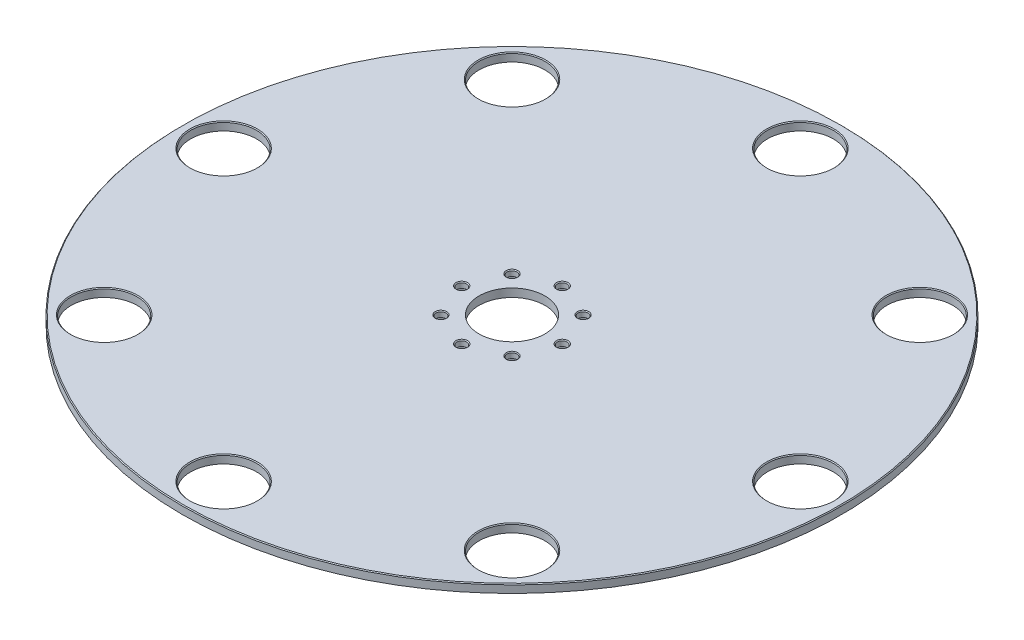
SolidWorks part; units mm, degrees
ref_plane "Front Plane" through (0, 0, 0) normal (0, 0, 1) x (1, 0, 0)
ref_plane "Top Plane" through (0, 0, 0) normal (0, 1, 0) x (1, 0, 0)
ref_plane "Right Plane" through (0, 0, 0) normal (1, 0, 0) x (0, 0, -1)
sketch "Sketch2" plane through (0, 0, 0) normal (0, 1, 0) x (1, 0, 0)
  line L0 (0, 409.7546) -> (0, -366.7272) construction
  line L1 (-380.7051, 0) -> (447.7899, 0) construction
  circle A0 centre (0, 0) radius 400
  circle A1 centre (0, 0) radius 40
  circle A2 centre (0, 350) radius 40
  circle A3 centre (247.4874, 247.4874) radius 40
  circle A4 centre (350, 0) radius 40
  circle A5 centre (247.4874, -247.4874) radius 40
  circle A6 centre (0, -350) radius 40
  circle A7 centre (-247.4874, -247.4874) radius 40
  circle A8 centre (-350, 0) radius 40
  circle A9 centre (-247.4874, 247.4874) radius 40
  point P26 (0, 0)
  point P52 (0, 0)
  dimension "D1" = 350
  dimension "D2" = 80
  dimension "D3" = 80
  dimension "D5" = 800
  dimension "D4" = 8
extrude "Boss-Extrude10" add sketch "Sketch2" along normal blind 10
chamfer "Chamfer1" distance 1 angle 45 9 edges at (-247.4874, 10, 287.4874) (0, 10, 390) (247.4874, 10, 287.4874) (350, 10, 40) (247.4874, 10, -207.4874) (0, 10, -310) (-247.4874, 10, -207.4874) (-350, 10, 40) (0, 10, 400)
sketch "Sketch13" plane through (0, 10, 0) normal (0, 1, 0) x (1, 0, 0)
  line L0 (0, 0) -> (-373.6419, 0) construction
  circle A0 centre (-61, 0) radius 6
  circle A1 centre (-43.1335, 43.1335) radius 6
  circle A2 centre (0, 61) radius 6
  circle A3 centre (43.1335, 43.1335) radius 6
  circle A4 centre (61, 0) radius 6
  circle A5 centre (43.1335, -43.1335) radius 6
  circle A6 centre (0, -61) radius 6
  circle A7 centre (-43.1335, -43.1335) radius 6
  point P21 (0, 0)
  dimension "D1" = 61
  dimension "D2" = 12
  dimension "D3" = 8
extrude "Cut-Extrude1" cut sketch "Sketch13" against normal blind 7
sketch "Sketch14" plane through (0, 0, 0) normal (0, -1, 0) x (1, 0, 0)
  line L0 (0, 0) -> (-132.8482, 0) construction
  circle A0 centre (-61, 0) radius 4
  circle A1 centre (-43.1335, 43.1335) radius 4
  circle A2 centre (0, 61) radius 4
  circle A3 centre (43.1335, 43.1335) radius 4
  circle A4 centre (61, 0) radius 4
  circle A5 centre (43.1335, -43.1335) radius 4
  circle A6 centre (0, -61) radius 4
  circle A7 centre (-43.1335, -43.1335) radius 4
  point P21 (0, 0)
  dimension "D1" = 61
  dimension "D2" = 8
  dimension "D3" = 8
chamfer "Chamfer2" distance 1 angle 45 8 edges at (0, 10, 67) (43.1335, 10, 49.1335) (61, 10, 6) (43.1335, 10, -37.1335) (0, 10, -55) (-43.1335, 10, -37.1335) (-61, 10, 6) (-43.1335, 10, 49.1335)
extrude "Cut-Extrude2" cut sketch "Sketch14" against normal blind 3
